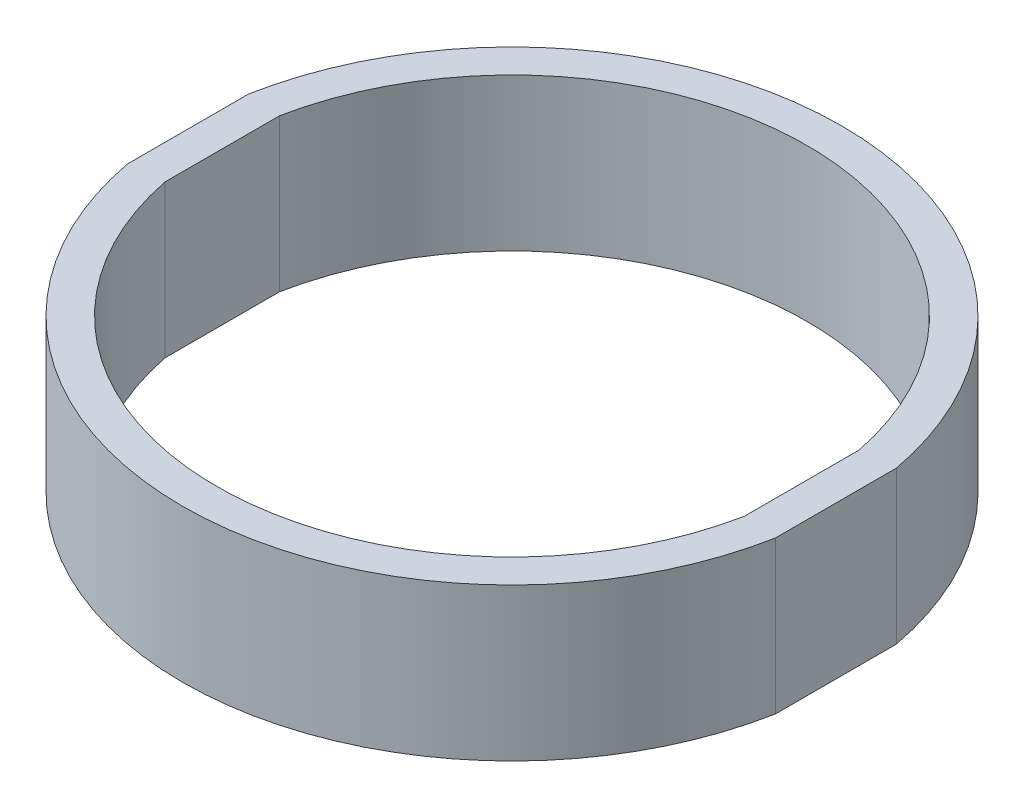
SolidWorks part; units mm, degrees
ref_plane "Front Plane" through (0, 0, 0) normal (0, 0, 1) x (1, 0, 0)
ref_plane "Top Plane" through (0, 0, 0) normal (0, 1, 0) x (1, 0, 0)
ref_plane "Right Plane" through (0, 0, 0) normal (1, 0, 0) x (0, 0, -1)
sketch "Sketch1" plane through (0, 0, 0) normal (0, 1, 0) x (1, 0, 0)
  line L0 (19, 0) -> (-19, 0) construction
  line L1 (19, 3.75) -> (19, -3.75)
  line L2 (-19, 3.75) -> (-19, -3.75)
  line L3 (-21.25, 3.9638) -> (-21.25, -3.9638)
  line L4 (21.25, 3.9638) -> (21.25, -3.9638)
  arc A0 (19, 3.75) -> (-19, 3.75) centre (0, 0) ccw
  arc A1 (-19, -3.75) -> (19, -3.75) centre (0, 0) ccw
  arc A2 (21.25, 3.9638) -> (-21.25, 3.9638) centre (0, 0) ccw
  arc A3 (-21.25, -3.9638) -> (21.25, -3.9638) centre (0, 0) ccw
  point P6 (0, 0)
  point P9 (19, 0)
  point P11 (-19, 0)
  dimension "D1" = 38
  dimension "D2" = 2.25
  dimension "D3" = 7.5
extrude "Boss-Extrude1" add sketch "Sketch1" along normal blind 10
